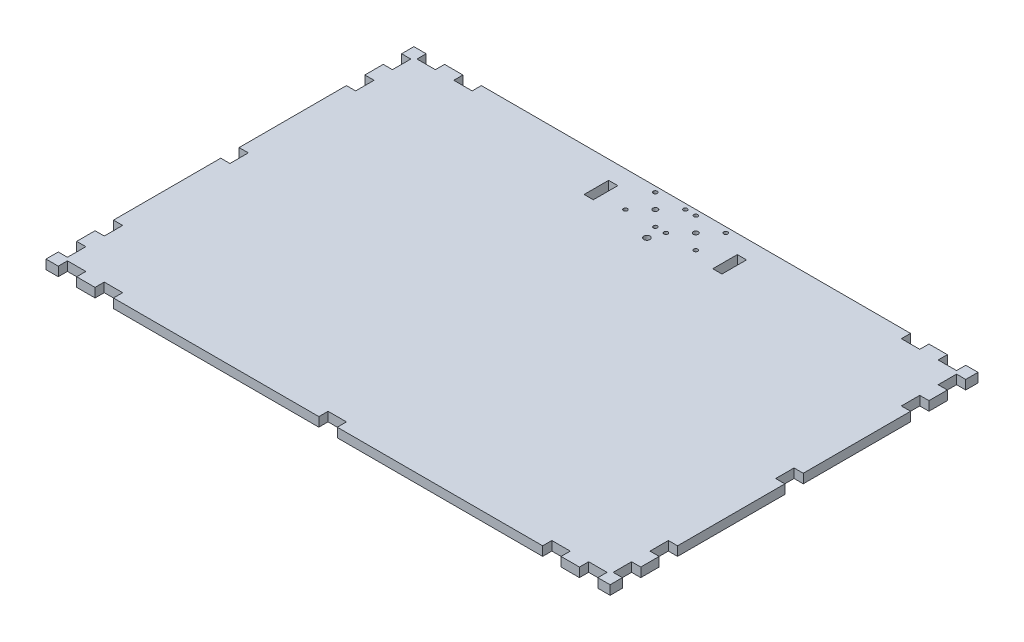
SolidWorks part; units mm, degrees
ref_plane "Front Plane" through (0, 0, 0) normal (0, 0, 1) x (1, 0, 0)
ref_plane "Top Plane" through (0, 0, 0) normal (0, 1, 0) x (1, 0, 0)
ref_plane "Right Plane" through (0, 0, 0) normal (1, 0, 0) x (0, 0, -1)
sketch "Sketch1" plane through (0, 0, 0) normal (0, 1, 0) x (1, 0, 0)
  line L1 (0, 0) -> (584.2, 0)
  line L2 (0, 0) -> (0, 381)
  line L3 (0, 381) -> (584.2, 381)
  line L4 (584.2, 0) -> (584.2, 381)
  dimension "D1" = 381
  dimension "D2" = 584.2
extrude "Boss-Extrude1" add sketch "Sketch1" along normal blind 9.525
sketch "Sketch2" plane through (0, 9.525, 0) normal (0, 1, 0) x (1, 0, 0)
  line L0 (0, 381) -> (0, 0) construction
  line L1 (0, 349.25) -> (9.525, 349.25)
  line L2 (0, 349.25) -> (0, 368.3)
  line L3 (0, 368.3) -> (9.525, 368.3)
  line L4 (9.525, 349.25) -> (9.525, 368.3)
  line L5 (584.2, 381) -> (0, 381) construction
  line L6 (12.7, 381) -> (31.75, 381)
  line L7 (12.7, 381) -> (12.7, 371.475)
  line L8 (12.7, 371.475) -> (31.75, 371.475)
  line L9 (31.75, 381) -> (31.75, 371.475)
  line L10 (292.1, 0) -> (292.1, 381) construction
  line L11 (0, 190.5) -> (584.2, 190.5) construction
  line L12 (584.2, 0) -> (584.2, 381) construction
  line L13 (0, 0) -> (584.2, 0) construction
  line L14 (571.5, 371.475) -> (552.45, 371.475)
  line L15 (552.45, 381) -> (552.45, 371.475)
  line L16 (571.5, 381) -> (552.45, 381)
  line L17 (571.5, 381) -> (571.5, 371.475)
  line L18 (584.2, 368.3) -> (574.675, 368.3)
  line L19 (574.675, 349.25) -> (574.675, 368.3)
  line L20 (584.2, 349.25) -> (574.675, 349.25)
  line L21 (584.2, 349.25) -> (584.2, 368.3)
  line L22 (584.2, 31.75) -> (584.2, 12.7)
  line L23 (584.2, 31.75) -> (574.675, 31.75)
  line L24 (574.675, 31.75) -> (574.675, 12.7)
  line L25 (584.2, 12.7) -> (574.675, 12.7)
  line L26 (571.5, 0) -> (571.5, 9.525)
  line L27 (571.5, 0) -> (552.45, 0)
  line L28 (552.45, 0) -> (552.45, 9.525)
  line L29 (571.5, 9.525) -> (552.45, 9.525)
  line L30 (0, 31.75) -> (9.525, 31.75)
  line L31 (9.525, 31.75) -> (9.525, 12.7)
  line L32 (0, 12.7) -> (9.525, 12.7)
  line L33 (0, 31.75) -> (0, 12.7)
  line L34 (12.7, 0) -> (31.75, 0)
  line L35 (31.75, 0) -> (31.75, 9.525)
  line L36 (12.7, 9.525) -> (31.75, 9.525)
  line L37 (12.7, 0) -> (12.7, 9.525)
  line L38 (282.575, 9.525) -> (301.625, 9.525)
  line L43 (301.625, 0) -> (301.625, 9.525)
  line L44 (282.575, 0) -> (301.625, 0)
  line L45 (282.575, 0) -> (282.575, 9.525)
  line L46 (0, 180.975) -> (9.525, 180.975)
  line L47 (584.2, 200.025) -> (574.675, 200.025)
  line L48 (584.2, 200.025) -> (584.2, 180.975)
  line L49 (584.2, 180.975) -> (574.675, 180.975)
  line L50 (574.675, 200.025) -> (574.675, 180.975)
  line L51 (9.525, 200.025) -> (9.525, 180.975)
  line L52 (0, 200.025) -> (9.525, 200.025)
  line L53 (0, 200.025) -> (0, 180.975)
  line L54 (50.8, 381) -> (50.8, 371.475)
  line L55 (50.8, 381) -> (69.85, 381)
  line L56 (69.85, 381) -> (69.85, 371.475)
  line L57 (50.8, 371.475) -> (69.85, 371.475)
  line L58 (0, 311.15) -> (0, 330.2)
  line L59 (0, 311.15) -> (9.525, 311.15)
  line L60 (9.525, 311.15) -> (9.525, 330.2)
  line L61 (0, 330.2) -> (9.525, 330.2)
  line L62 (533.4, 371.475) -> (514.35, 371.475)
  line L63 (514.35, 381) -> (514.35, 371.475)
  line L64 (533.4, 381) -> (514.35, 381)
  line L65 (533.4, 381) -> (533.4, 371.475)
  line L66 (584.2, 330.2) -> (574.675, 330.2)
  line L67 (574.675, 311.15) -> (574.675, 330.2)
  line L68 (584.2, 311.15) -> (574.675, 311.15)
  line L69 (584.2, 311.15) -> (584.2, 330.2)
  line L70 (584.2, 69.85) -> (584.2, 50.8)
  line L71 (584.2, 50.8) -> (574.675, 50.8)
  line L72 (574.675, 69.85) -> (574.675, 50.8)
  line L73 (584.2, 69.85) -> (574.675, 69.85)
  line L74 (533.4, 0) -> (533.4, 9.525)
  line L75 (533.4, 9.525) -> (514.35, 9.525)
  line L76 (514.35, 0) -> (514.35, 9.525)
  line L77 (533.4, 0) -> (514.35, 0)
  line L78 (0, 69.85) -> (9.525, 69.85)
  line L79 (9.525, 69.85) -> (9.525, 50.8)
  line L80 (0, 50.8) -> (9.525, 50.8)
  line L81 (0, 69.85) -> (0, 50.8)
  line L82 (50.8, 0) -> (69.85, 0)
  line L83 (69.85, 0) -> (69.85, 9.525)
  line L84 (50.8, 9.525) -> (69.85, 9.525)
  line L85 (50.8, 0) -> (50.8, 9.525)
  dimension "D1" = 9.525
  dimension "D2" = 19.05
  dimension "D3" = 9.525
  dimension "D4" = 19.05
  dimension "D5" = 12.7
  dimension "D6" = 12.7
  dimension "D7" = 9.525
  dimension "D8" = 19.05
  dimension "D9" = 19.05
  dimension "D10" = 9.525
  dimension "D11" = 2
  dimension "D12" = 2
  dimension "D13" = 2
  dimension "D14" = 2
  dimension "D15" = 2
  dimension "D16" = 2
  dimension "D17" = 2
  dimension "D18" = 2
extrude "Cut-Extrude1" cut sketch "Sketch2" against normal through all contours L2 L1 L4 L3 | L14 L15 L16 L17 | L18 L19 L20 L21 | L26 L29 L28 L27 | L22 L25 L24 L23 | L30 L31 L32 L33 | L34 L35 L36 L37 | L48 L47 L50 L49 | L38 L43 L44 L45 | L46 L51 L52 L53 | L54 L57 L56 L55 | L58 L61 L60 L59 | L82 L83 L84 L85 | L78 L79 L80 L81 | L74 L75 L76 L77 | L70 L71 L72 L73 | L66 L67 L68 L69 | L62 L63 L64 L65 | L7 L6 L9 L8
sketch "Sketch3" plane through (0, 9.525, 0) normal (0, 1, 0) x (1, 0, 0)
  line L0 (514.35, 381) -> (69.85, 381) construction
  line L1 (292.1, 381) -> (292.1, 330.2) construction
  line L2 (353.949, 336.55) -> (363.474, 336.55)
  line L3 (230.251, 361.95) -> (220.726, 361.95)
  line L4 (230.251, 361.95) -> (230.251, 336.55)
  line L5 (230.251, 336.55) -> (220.726, 336.55)
  line L6 (271.145, 357.378) -> (271.145, 362.458) construction
  line L7 (268.605, 359.918) -> (273.685, 359.918) construction
  line L8 (220.726, 361.95) -> (220.726, 336.55)
  line L9 (363.474, 361.95) -> (363.474, 336.55)
  line L10 (353.949, 361.95) -> (363.474, 361.95)
  line L11 (353.949, 361.95) -> (353.949, 336.55)
  circle A0 centre (255.651, 375.412) radius 2.032
  circle A1 centre (328.549, 375.412) radius 2.032
  circle A2 centre (286.639, 375.412) radius 2.032
  circle A3 centre (297.561, 375.412) radius 2.032
  circle A4 centre (255.651, 344.424) radius 2.032
  circle A5 centre (286.639, 344.424) radius 2.032
  circle A6 centre (297.561, 344.424) radius 2.032
  circle A7 centre (328.549, 344.424) radius 2.032
  circle A8 centre (271.145, 359.918) radius 2.54
  circle A9 centre (313.055, 359.918) radius 2.54
  circle A10 centre (292.1, 330.2) radius 3.175
  dimension "D1" = 4.064
  dimension "D7" = 5.08
  dimension "D10" = 6.35
  dimension "D2" = 72.898
  dimension "D3" = 5.588
  dimension "D4" = 30.988
  dimension "D5" = 30.988
  dimension "D6" = 30.988
  dimension "D8" = 15.494
  dimension "D9" = 15.494
  dimension "D11" = 50.8
  dimension "D12" = 25.4
  dimension "D13" = 9.525
  dimension "D14" = 19.05
  dimension "D15" = 25.4
extrude "Cut-Extrude2" cut sketch "Sketch3" against normal through all
